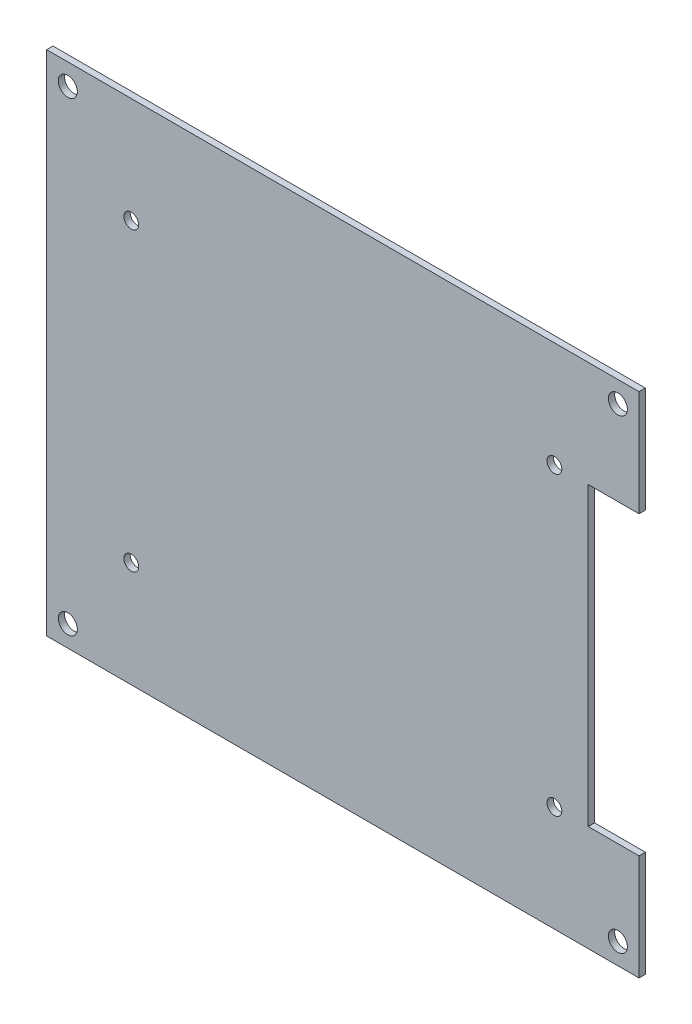
SolidWorks part; units mm, degrees
ref_plane "Спереди" through (0, 0, 0) normal (0, 0, 1) x (1, 0, 0)
ref_plane "Сверху" through (0, 0, 0) normal (0, 1, 0) x (1, 0, 0)
ref_plane "Справа" through (0, 0, 0) normal (1, 0, 0) x (0, 0, -1)
sketch "Эскиз1" plane through (0, 0, 0) normal (0, 0, 1) x (1, 0, 0)
  line L0 (0, 42.3611) -> (0, -41.9385) construction
  line L1 (-61.5264, 0) -> (36.4139, 0) construction
  line L2 (50, -35) -> (50, 35) construction
  line L3 (-70, -60) -> (70, -60)
  line L4 (-70, -60) -> (-70, 60)
  line L5 (-70, 60) -> (70, 60)
  line L6 (70, -60) -> (70, 60)
  circle A0 centre (-65, 55) radius 2.25
  circle A1 centre (-65, -55) radius 2.25
  circle A2 centre (65, -55) radius 2.25
  circle A3 centre (65, 55) radius 2.25
  circle A4 centre (-50, 35) radius 1.75
  circle A5 centre (-50, -35) radius 1.75
  circle A6 centre (50, 35) radius 1.75
  circle A7 centre (50, -35) radius 1.75
  dimension "D3" = 5
  dimension "D5" = 110
  dimension "D8" = 3.5
  dimension "D10" = 70
  dimension "D4" = 25
  dimension "D7" = 100
  dimension "D6" = 70
  dimension "D12" = 100
  dimension "D9" = 4.5
  dimension "D1" = 140
  dimension "D2" = 120
extrude "Вытянуть1" add sketch "Эскиз1" along normal blind 1.5
sketch "Эскиз2" plane through (0, 0, 1.5) normal (0, 0, 1) x (1, 0, 0)
  line L0 (0, 0) -> (-76.1135, 0) construction
  line L2 (79.1242, -35) -> (58, -35)
  line L3 (79.1242, -35) -> (79.1242, 35)
  line L4 (79.1242, 35) -> (58, 35)
  line L5 (58, -35) -> (58, 35)
  line L6 (70, -60) -> (70, 60) construction
  dimension "D1" = 70
  dimension "D2" = 12
extrude "Вырез-Вытянуть1" cut sketch "Эскиз2" against normal blind 10
